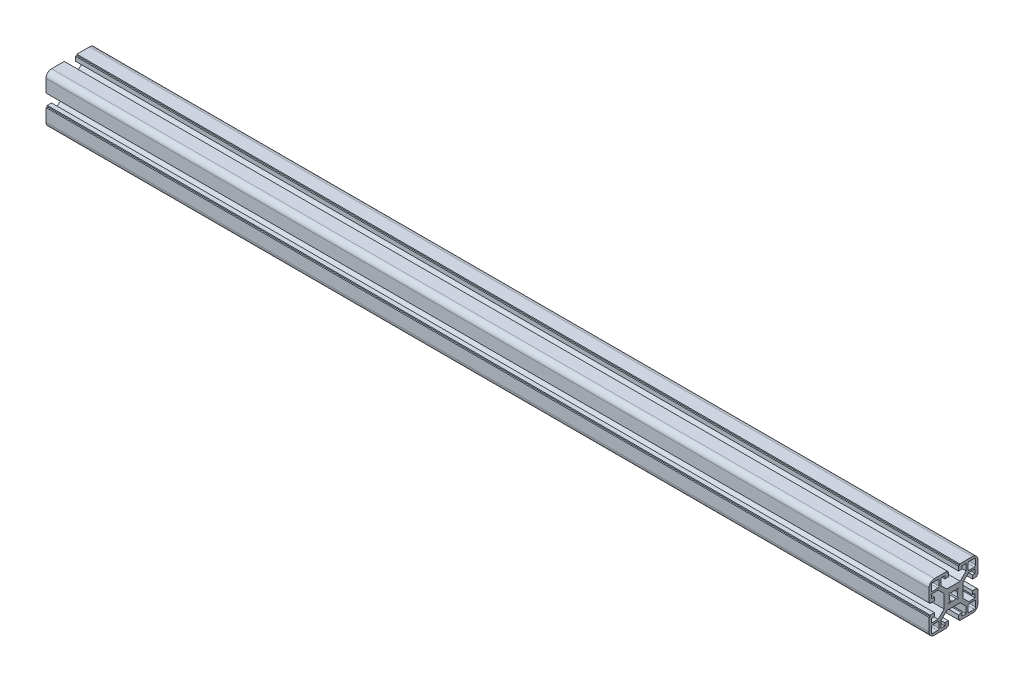
SolidWorks part; units mm, degrees
ref_plane "前视基准面" through (0, 0, 0) normal (0, 0, 1) x (1, 0, 0)
ref_plane "上视基准面" through (0, 0, 0) normal (0, 1, 0) x (1, 0, 0)
ref_plane "右视基准面" through (0, 0, 0) normal (1, 0, 0) x (0, 0, -1)
other "Configuration Table"
sketch "草图1" plane through (0, 0, 0) normal (1, 0, 0) x (0, 0, -1)
  line L0 (4.82, 19.28) -> (3.82, 19.28)
  line L1 (3.82, 19.28) -> (3.82, 15.78)
  line L2 (3.82, 15.78) -> (6.7364, 15.78)
  line L3 (6.7364, 15.78) -> (6.7364, 18.03)
  line L4 (6.7364, 18.03) -> (10.02, 18.03)
  line L5 (10.02, 18.03) -> (10.02, 12.7013)
  line L6 (10.02, 12.7013) -> (5.1987, 7.88)
  line L7 (5.1987, 7.88) -> (-5.7586, 7.88)
  line L8 (-5.7586, 7.88) -> (-10.58, 12.7013)
  line L9 (-10.58, 12.7013) -> (-10.58, 18.03)
  line L10 (-10.58, 18.03) -> (-7.2963, 18.03)
  line L11 (-7.2963, 18.03) -> (-7.2963, 15.78)
  line L12 (-7.2963, 15.78) -> (-4.38, 15.78)
  line L13 (-4.38, 15.78) -> (-4.38, 19.28)
  line L14 (-4.38, 19.28) -> (-5.38, 19.28)
  line L15 (-5.38, 19.28) -> (-5.38, 20.28)
  line L16 (-5.38, 20.28) -> (-15.78, 20.28)
  line L17 (-20.28, 15.78) -> (-20.28, 5.38)
  line L18 (-20.28, 5.38) -> (-19.28, 5.38)
  line L19 (-19.28, 5.38) -> (-19.28, 4.38)
  line L20 (-19.28, 4.38) -> (-15.78, 4.38)
  line L21 (-15.78, 4.38) -> (-15.78, 7.2963)
  line L22 (-15.78, 7.2963) -> (-18.03, 7.2963)
  line L23 (-18.03, 7.2963) -> (-18.03, 10.58)
  line L24 (-18.03, 10.58) -> (-12.7013, 10.58)
  line L25 (-12.7013, 10.58) -> (-7.88, 5.7586)
  line L26 (-7.88, 5.7586) -> (-7.88, -5.1987)
  line L27 (-7.88, -5.1987) -> (-12.7013, -10.02)
  line L28 (-12.7013, -10.02) -> (-18.03, -10.02)
  line L29 (-18.03, -10.02) -> (-18.03, -6.7364)
  line L30 (-18.03, -6.7364) -> (-15.78, -6.7364)
  line L31 (-15.78, -6.7364) -> (-15.78, -3.82)
  line L32 (-15.78, -3.82) -> (-19.28, -3.82)
  line L33 (-19.28, -3.82) -> (-19.28, -4.82)
  line L34 (-19.28, -4.82) -> (-20.28, -4.82)
  line L35 (-20.28, -4.82) -> (-20.28, -15.22)
  line L36 (-15.78, -19.72) -> (-5.38, -19.72)
  line L37 (-5.38, -19.72) -> (-5.38, -18.72)
  line L38 (-5.38, -18.72) -> (-4.38, -18.72)
  line L39 (-4.38, -18.72) -> (-4.38, -15.22)
  line L40 (-4.38, -15.22) -> (-7.2963, -15.22)
  line L41 (-7.2963, -15.22) -> (-7.2963, -17.47)
  line L42 (-7.2963, -17.47) -> (-10.58, -17.47)
  line L43 (-10.58, -17.47) -> (-10.58, -12.1414)
  line L44 (-10.58, -12.1414) -> (-5.7586, -7.32)
  line L45 (-5.7586, -7.32) -> (5.1987, -7.32)
  line L46 (5.1987, -7.32) -> (10.02, -12.1414)
  line L47 (10.02, -12.1414) -> (10.02, -17.47)
  line L48 (10.02, -17.47) -> (6.7364, -17.47)
  line L49 (6.7364, -17.47) -> (6.7364, -15.22)
  line L50 (6.7364, -15.22) -> (3.82, -15.22)
  line L51 (3.82, -15.22) -> (3.82, -18.72)
  line L52 (3.82, -18.72) -> (4.82, -18.72)
  line L53 (4.82, -18.72) -> (4.82, -19.72)
  line L54 (4.82, -19.72) -> (15.22, -19.72)
  line L55 (19.72, -15.22) -> (19.72, -4.82)
  line L56 (19.72, -4.82) -> (18.72, -4.82)
  line L57 (18.72, -4.82) -> (18.72, -3.82)
  line L58 (18.72, -3.82) -> (15.22, -3.82)
  line L59 (15.22, -3.82) -> (15.22, -6.7364)
  line L60 (15.22, -6.7364) -> (17.47, -6.7364)
  line L61 (17.47, -6.7364) -> (17.47, -10.02)
  line L62 (17.47, -10.02) -> (12.1414, -10.02)
  line L63 (12.1414, -10.02) -> (7.32, -5.1987)
  line L64 (7.32, -5.1987) -> (7.32, 5.7586)
  line L65 (7.32, 5.7586) -> (12.1414, 10.58)
  line L66 (12.1414, 10.58) -> (17.47, 10.58)
  line L67 (17.47, 10.58) -> (17.47, 7.2963)
  line L68 (17.47, 7.2963) -> (15.22, 7.2963)
  line L69 (15.22, 7.2963) -> (15.22, 4.38)
  line L70 (15.22, 4.38) -> (18.72, 4.38)
  line L71 (18.72, 4.38) -> (18.72, 5.38)
  line L72 (18.72, 5.38) -> (19.72, 5.38)
  line L73 (19.72, 5.38) -> (19.72, 15.78)
  line L74 (15.22, 20.28) -> (4.82, 20.28)
  line L75 (4.82, 20.28) -> (4.82, 19.28)
  line L76 (-13.08, -17.72) -> (-17.28, -17.72)
  line L77 (-18.28, -16.72) -> (-18.28, -12.52)
  line L78 (-17.28, -11.52) -> (-13.08, -11.52)
  line L79 (-12.08, -12.52) -> (-12.08, -16.72)
  line L80 (-17.28, 18.28) -> (-13.08, 18.28)
  line L81 (-12.08, 17.28) -> (-12.08, 13.08)
  line L82 (-13.08, 12.08) -> (-17.28, 12.08)
  line L83 (-18.28, 13.08) -> (-18.28, 17.28)
  line L84 (16.72, 12.08) -> (12.52, 12.08)
  line L85 (11.52, 13.08) -> (11.52, 17.28)
  line L86 (12.52, 18.28) -> (16.72, 18.28)
  line L87 (17.72, 17.28) -> (17.72, 13.08)
  line L88 (3.7505, -3.0434) -> (3.0434, -3.7505)
  line L89 (3.0434, -3.7505) -> (1.7445, -2.4516)
  line L90 (-2.3044, -2.4516) -> (-3.6033, -3.7505)
  line L91 (-3.6033, -3.7505) -> (-4.3104, -3.0434)
  line L92 (-4.3104, -3.0434) -> (-3.0115, -1.7445)
  line L93 (-3.0115, 2.3044) -> (-4.3104, 3.6033)
  line L94 (-4.3104, 3.6033) -> (-3.6033, 4.3104)
  line L95 (-3.6033, 4.3104) -> (-2.3044, 3.0115)
  line L96 (1.7445, 3.0115) -> (3.0434, 4.3104)
  line L97 (3.0434, 4.3104) -> (3.7505, 3.6033)
  line L98 (3.7505, 3.6033) -> (2.4516, 2.3044)
  line L99 (2.4516, -1.7445) -> (3.7505, -3.0434)
  line L100 (17.72, -12.52) -> (17.72, -16.72)
  line L101 (16.72, -17.72) -> (12.52, -17.72)
  line L102 (11.52, -16.72) -> (11.52, -12.52)
  line L103 (12.52, -11.52) -> (16.72, -11.52)
  arc A0 (-15.78, 20.28) -> (-20.28, 15.78) centre (-15.78, 15.78) ccw
  arc A1 (-20.28, -15.22) -> (-15.78, -19.72) centre (-15.78, -15.22) ccw
  arc A2 (15.22, -19.72) -> (19.72, -15.22) centre (15.22, -15.22) ccw
  arc A3 (19.72, 15.78) -> (15.22, 20.28) centre (15.22, 15.78) ccw
  arc A4 (-12.08, -16.72) -> (-13.08, -17.72) centre (-13.08, -16.72) cw
  arc A5 (-17.28, -17.72) -> (-18.28, -16.72) centre (-17.28, -16.72) cw
  arc A6 (-18.28, -12.52) -> (-17.28, -11.52) centre (-17.28, -12.52) cw
  arc A7 (-13.08, -11.52) -> (-12.08, -12.52) centre (-13.08, -12.52) cw
  arc A8 (-18.28, 17.28) -> (-17.28, 18.28) centre (-17.28, 17.28) cw
  arc A9 (-13.08, 18.28) -> (-12.08, 17.28) centre (-13.08, 17.28) cw
  arc A10 (-12.08, 13.08) -> (-13.08, 12.08) centre (-13.08, 13.08) cw
  arc A11 (-17.28, 12.08) -> (-18.28, 13.08) centre (-17.28, 13.08) cw
  arc A12 (17.72, 13.08) -> (16.72, 12.08) centre (16.72, 13.08) cw
  arc A13 (12.52, 12.08) -> (11.52, 13.08) centre (12.52, 13.08) cw
  arc A14 (11.52, 17.28) -> (12.52, 18.28) centre (12.52, 17.28) cw
  arc A15 (16.72, 18.28) -> (17.72, 17.28) centre (16.72, 17.28) cw
  arc A16 (1.7445, -2.4516) -> (-2.3044, -2.4516) centre (-0.28, 0.28) cw
  arc A17 (-3.0115, -1.7445) -> (-3.0115, 2.3044) centre (-0.28, 0.28) cw
  arc A18 (-2.3044, 3.0115) -> (1.7445, 3.0115) centre (-0.28, 0.28) cw
  arc A19 (2.4516, 2.3044) -> (2.4516, -1.7445) centre (-0.28, 0.28) cw
  arc A20 (16.72, -11.52) -> (17.72, -12.52) centre (16.72, -12.52) cw
  arc A21 (17.72, -16.72) -> (16.72, -17.72) centre (16.72, -16.72) cw
  arc A22 (12.52, -17.72) -> (11.52, -16.72) centre (12.52, -16.72) cw
  arc A23 (11.52, -12.52) -> (12.52, -11.52) centre (12.52, -12.52) cw
extrude "凸台-拉伸1" add sketch "草图1" against normal blind 50
sketch "草图2" plane through (0, 0, 0) normal (1, 0, 0) x (0, 0, -1)
  line L4 (-17.28, -17.72) -> (-13.08, -17.72)
  line L5 (-18.28, -12.52) -> (-18.28, -16.72)
  line L6 (-13.08, -11.52) -> (-17.28, -11.52)
  line L7 (-12.08, -16.72) -> (-12.08, -12.52)
  line L8 (-17.28, -17.72) -> (-13.08, -17.72)
  line L9 (-18.28, -12.52) -> (-18.28, -16.72)
  line L10 (-13.08, -11.52) -> (-17.28, -11.52)
  line L11 (-12.08, -16.72) -> (-12.08, -12.52)
  line L12 (-13.08, 18.28) -> (-17.28, 18.28)
  line L13 (-12.08, 13.08) -> (-12.08, 17.28)
  line L14 (-17.28, 12.08) -> (-13.08, 12.08)
  line L15 (-18.28, 17.28) -> (-18.28, 13.08)
  line L16 (-13.08, 18.28) -> (-17.28, 18.28)
  line L17 (-12.08, 13.08) -> (-12.08, 17.28)
  line L18 (-17.28, 12.08) -> (-13.08, 12.08)
  line L19 (-18.28, 17.28) -> (-18.28, 13.08)
  line L20 (11.52, 17.28) -> (11.52, 13.08)
  line L21 (16.72, 18.28) -> (12.52, 18.28)
  line L22 (17.72, 13.08) -> (17.72, 17.28)
  line L23 (12.52, 12.08) -> (16.72, 12.08)
  line L24 (11.52, 17.28) -> (11.52, 13.08)
  line L25 (16.72, 18.28) -> (12.52, 18.28)
  line L26 (17.72, 13.08) -> (17.72, 17.28)
  line L27 (12.52, 12.08) -> (16.72, 12.08)
  line L28 (11.52, -12.52) -> (11.52, -16.72)
  line L29 (16.72, -11.52) -> (12.52, -11.52)
  line L30 (17.72, -16.72) -> (17.72, -12.52)
  line L31 (12.52, -17.72) -> (16.72, -17.72)
  line L32 (11.52, -12.52) -> (11.52, -16.72)
  line L33 (16.72, -11.52) -> (12.52, -11.52)
  line L34 (17.72, -16.72) -> (17.72, -12.52)
  line L35 (12.52, -17.72) -> (16.72, -17.72)
  line L36 (-4.3104, 3.6033) -> (-3.0115, 2.3044)
  line L37 (-3.6033, 4.3104) -> (-4.3104, 3.6033)
  line L38 (-2.3044, 3.0115) -> (-3.6033, 4.3104)
  line L39 (3.0434, 4.3104) -> (1.7445, 3.0115)
  line L40 (3.7505, 3.6033) -> (3.0434, 4.3104)
  line L41 (2.4516, 2.3044) -> (3.7505, 3.6033)
  line L42 (3.7505, -3.0434) -> (2.4516, -1.7445)
  line L43 (3.0434, -3.7505) -> (3.7505, -3.0434)
  line L44 (1.7445, -2.4516) -> (3.0434, -3.7505)
  line L45 (-3.6033, -3.7505) -> (-2.3044, -2.4516)
  line L46 (-4.3104, -3.0434) -> (-3.6033, -3.7505)
  line L47 (-3.0115, -1.7445) -> (-4.3104, -3.0434)
  line L48 (-4.3104, 3.6033) -> (-3.0115, 2.3044)
  line L49 (-3.6033, 4.3104) -> (-4.3104, 3.6033)
  line L50 (-2.3044, 3.0115) -> (-3.6033, 4.3104)
  line L51 (3.0434, 4.3104) -> (1.7445, 3.0115)
  line L52 (3.7505, 3.6033) -> (3.0434, 4.3104)
  line L53 (2.4516, 2.3044) -> (3.7505, 3.6033)
  line L54 (3.7505, -3.0434) -> (2.4516, -1.7445)
  line L55 (3.0434, -3.7505) -> (3.7505, -3.0434)
  line L56 (1.7445, -2.4516) -> (3.0434, -3.7505)
  line L57 (-3.6033, -3.7505) -> (-2.3044, -2.4516)
  line L58 (-4.3104, -3.0434) -> (-3.6033, -3.7505)
  line L59 (-3.0115, -1.7445) -> (-4.3104, -3.0434)
  line L84 (19.72, 5.38) -> (19.72, 15.78)
  line L85 (18.72, 5.38) -> (19.72, 5.38)
  line L86 (18.72, 4.38) -> (18.72, 5.38)
  line L87 (15.22, 4.38) -> (18.72, 4.38)
  line L88 (15.22, 7.2963) -> (15.22, 4.38)
  line L89 (17.47, 7.2963) -> (15.22, 7.2963)
  line L90 (17.47, 10.58) -> (17.47, 7.2963)
  line L91 (12.1414, 10.58) -> (17.47, 10.58)
  line L92 (7.32, 5.7586) -> (12.1414, 10.58)
  line L93 (7.32, -5.1987) -> (7.32, 5.7586)
  line L94 (12.1414, -10.02) -> (7.32, -5.1987)
  line L95 (17.47, -10.02) -> (12.1414, -10.02)
  line L96 (17.47, -6.7364) -> (17.47, -10.02)
  line L97 (15.22, -6.7364) -> (17.47, -6.7364)
  line L98 (15.22, -3.82) -> (15.22, -6.7364)
  line L99 (18.72, -3.82) -> (15.22, -3.82)
  line L100 (18.72, -4.82) -> (18.72, -3.82)
  line L101 (19.72, -4.82) -> (18.72, -4.82)
  line L102 (19.72, -15.22) -> (19.72, -4.82)
  line L103 (4.82, -19.72) -> (15.22, -19.72)
  line L104 (4.82, -18.72) -> (4.82, -19.72)
  line L105 (3.82, -18.72) -> (4.82, -18.72)
  line L106 (3.82, -15.22) -> (3.82, -18.72)
  line L107 (6.7364, -15.22) -> (3.82, -15.22)
  line L108 (6.7364, -17.47) -> (6.7364, -15.22)
  line L109 (10.02, -17.47) -> (6.7364, -17.47)
  line L110 (10.02, -12.1414) -> (10.02, -17.47)
  line L111 (5.1987, -7.32) -> (10.02, -12.1414)
  line L112 (-5.7586, -7.32) -> (5.1987, -7.32)
  line L113 (-10.58, -12.1414) -> (-5.7586, -7.32)
  line L114 (-10.58, -17.47) -> (-10.58, -12.1414)
  line L115 (-7.2963, -17.47) -> (-10.58, -17.47)
  line L116 (-7.2963, -15.22) -> (-7.2963, -17.47)
  line L117 (-4.38, -15.22) -> (-7.2963, -15.22)
  line L118 (-4.38, -18.72) -> (-4.38, -15.22)
  line L119 (-5.38, -18.72) -> (-4.38, -18.72)
  line L120 (-5.38, -19.72) -> (-5.38, -18.72)
  line L121 (-15.78, -19.72) -> (-5.38, -19.72)
  line L122 (-20.28, -4.82) -> (-20.28, -15.22)
  line L123 (-19.28, -4.82) -> (-20.28, -4.82)
  line L124 (-19.28, -3.82) -> (-19.28, -4.82)
  line L125 (-15.78, -3.82) -> (-19.28, -3.82)
  line L126 (-15.78, -6.7364) -> (-15.78, -3.82)
  line L127 (-18.03, -6.7364) -> (-15.78, -6.7364)
  line L128 (-18.03, -10.02) -> (-18.03, -6.7364)
  line L129 (-12.7013, -10.02) -> (-18.03, -10.02)
  line L130 (-7.88, -5.1987) -> (-12.7013, -10.02)
  line L131 (-7.88, 5.7586) -> (-7.88, -5.1987)
  line L132 (-12.7013, 10.58) -> (-7.88, 5.7586)
  line L133 (-18.03, 10.58) -> (-12.7013, 10.58)
  line L134 (-18.03, 7.2963) -> (-18.03, 10.58)
  line L135 (-15.78, 7.2963) -> (-18.03, 7.2963)
  line L136 (-15.78, 4.38) -> (-15.78, 7.2963)
  line L137 (-19.28, 4.38) -> (-15.78, 4.38)
  line L138 (-19.28, 5.38) -> (-19.28, 4.38)
  line L139 (-20.28, 5.38) -> (-19.28, 5.38)
  line L140 (-20.28, 15.78) -> (-20.28, 5.38)
  line L141 (-5.38, 20.28) -> (-15.78, 20.28)
  line L142 (-5.38, 19.28) -> (-5.38, 20.28)
  line L143 (-4.38, 19.28) -> (-5.38, 19.28)
  line L144 (-4.38, 15.78) -> (-4.38, 19.28)
  line L145 (-7.2963, 15.78) -> (-4.38, 15.78)
  line L146 (-7.2963, 18.03) -> (-7.2963, 15.78)
  line L147 (-10.58, 18.03) -> (-7.2963, 18.03)
  line L148 (-10.58, 12.7013) -> (-10.58, 18.03)
  line L149 (-5.7586, 7.88) -> (-10.58, 12.7013)
  line L150 (5.1987, 7.88) -> (-5.7586, 7.88)
  line L151 (10.02, 12.7013) -> (5.1987, 7.88)
  line L152 (10.02, 18.03) -> (10.02, 12.7013)
  line L153 (6.7364, 18.03) -> (10.02, 18.03)
  line L154 (6.7364, 15.78) -> (6.7364, 18.03)
  line L155 (3.82, 15.78) -> (6.7364, 15.78)
  line L156 (3.82, 19.28) -> (3.82, 15.78)
  line L157 (4.82, 19.28) -> (3.82, 19.28)
  line L158 (4.82, 20.28) -> (4.82, 19.28)
  line L159 (15.22, 20.28) -> (4.82, 20.28)
  line L160 (19.72, 5.38) -> (19.72, 15.78)
  line L161 (18.72, 5.38) -> (19.72, 5.38)
  line L162 (18.72, 4.38) -> (18.72, 5.38)
  line L163 (15.22, 4.38) -> (18.72, 4.38)
  line L164 (15.22, 7.2963) -> (15.22, 4.38)
  line L165 (17.47, 7.2963) -> (15.22, 7.2963)
  line L166 (17.47, 10.58) -> (17.47, 7.2963)
  line L167 (12.1414, 10.58) -> (17.47, 10.58)
  line L168 (7.32, 5.7586) -> (12.1414, 10.58)
  line L169 (7.32, -5.1987) -> (7.32, 5.7586)
  line L170 (12.1414, -10.02) -> (7.32, -5.1987)
  line L171 (17.47, -10.02) -> (12.1414, -10.02)
  line L172 (17.47, -6.7364) -> (17.47, -10.02)
  line L173 (15.22, -6.7364) -> (17.47, -6.7364)
  line L174 (15.22, -3.82) -> (15.22, -6.7364)
  line L175 (18.72, -3.82) -> (15.22, -3.82)
  line L176 (18.72, -4.82) -> (18.72, -3.82)
  line L177 (19.72, -4.82) -> (18.72, -4.82)
  line L178 (19.72, -15.22) -> (19.72, -4.82)
  line L179 (4.82, -19.72) -> (15.22, -19.72)
  line L180 (4.82, -18.72) -> (4.82, -19.72)
  line L181 (3.82, -18.72) -> (4.82, -18.72)
  line L182 (3.82, -15.22) -> (3.82, -18.72)
  line L183 (6.7364, -15.22) -> (3.82, -15.22)
  line L184 (6.7364, -17.47) -> (6.7364, -15.22)
  line L185 (10.02, -17.47) -> (6.7364, -17.47)
  line L186 (10.02, -12.1414) -> (10.02, -17.47)
  line L187 (5.1987, -7.32) -> (10.02, -12.1414)
  line L188 (-5.7586, -7.32) -> (5.1987, -7.32)
  line L189 (-10.58, -12.1414) -> (-5.7586, -7.32)
  line L190 (-10.58, -17.47) -> (-10.58, -12.1414)
  line L191 (-7.2963, -17.47) -> (-10.58, -17.47)
  line L192 (-7.2963, -15.22) -> (-7.2963, -17.47)
  line L193 (-4.38, -15.22) -> (-7.2963, -15.22)
  line L194 (-4.38, -18.72) -> (-4.38, -15.22)
  line L195 (-5.38, -18.72) -> (-4.38, -18.72)
  line L196 (-5.38, -19.72) -> (-5.38, -18.72)
  line L197 (-15.78, -19.72) -> (-5.38, -19.72)
  line L198 (-20.28, -4.82) -> (-20.28, -15.22)
  line L199 (-19.28, -4.82) -> (-20.28, -4.82)
  line L200 (-19.28, -3.82) -> (-19.28, -4.82)
  line L201 (-15.78, -3.82) -> (-19.28, -3.82)
  line L202 (-15.78, -6.7364) -> (-15.78, -3.82)
  line L203 (-18.03, -6.7364) -> (-15.78, -6.7364)
  line L204 (-18.03, -10.02) -> (-18.03, -6.7364)
  line L205 (-12.7013, -10.02) -> (-18.03, -10.02)
  line L206 (-7.88, -5.1987) -> (-12.7013, -10.02)
  line L207 (-7.88, 5.7586) -> (-7.88, -5.1987)
  line L208 (-12.7013, 10.58) -> (-7.88, 5.7586)
  line L209 (-18.03, 10.58) -> (-12.7013, 10.58)
  line L210 (-18.03, 7.2963) -> (-18.03, 10.58)
  line L211 (-15.78, 7.2963) -> (-18.03, 7.2963)
  line L212 (-15.78, 4.38) -> (-15.78, 7.2963)
  line L213 (-19.28, 4.38) -> (-15.78, 4.38)
  line L214 (-19.28, 5.38) -> (-19.28, 4.38)
  line L215 (-20.28, 5.38) -> (-19.28, 5.38)
  line L216 (-20.28, 15.78) -> (-20.28, 5.38)
  line L217 (-5.38, 20.28) -> (-15.78, 20.28)
  line L218 (-5.38, 19.28) -> (-5.38, 20.28)
  line L219 (-4.38, 19.28) -> (-5.38, 19.28)
  line L220 (-4.38, 15.78) -> (-4.38, 19.28)
  line L221 (-7.2963, 15.78) -> (-4.38, 15.78)
  line L222 (-7.2963, 18.03) -> (-7.2963, 15.78)
  line L223 (-10.58, 18.03) -> (-7.2963, 18.03)
  line L224 (-10.58, 12.7013) -> (-10.58, 18.03)
  line L225 (-5.7586, 7.88) -> (-10.58, 12.7013)
  line L226 (5.1987, 7.88) -> (-5.7586, 7.88)
  line L227 (10.02, 12.7013) -> (5.1987, 7.88)
  line L228 (10.02, 18.03) -> (10.02, 12.7013)
  line L229 (6.7364, 18.03) -> (10.02, 18.03)
  line L230 (6.7364, 15.78) -> (6.7364, 18.03)
  line L231 (3.82, 15.78) -> (6.7364, 15.78)
  line L232 (3.82, 19.28) -> (3.82, 15.78)
  line L233 (4.82, 19.28) -> (3.82, 19.28)
  line L234 (4.82, 20.28) -> (4.82, 19.28)
  line L235 (15.22, 20.28) -> (4.82, 20.28)
  arc A4 (-18.28, -16.72) -> (-17.28, -17.72) centre (-17.28, -16.72) ccw
  arc A5 (-17.28, -11.52) -> (-18.28, -12.52) centre (-17.28, -12.52) ccw
  arc A6 (-12.08, -12.52) -> (-13.08, -11.52) centre (-13.08, -12.52) ccw
  arc A7 (-13.08, -17.72) -> (-12.08, -16.72) centre (-13.08, -16.72) ccw
  arc A8 (-18.28, -16.72) -> (-17.28, -17.72) centre (-17.28, -16.72) ccw
  arc A9 (-17.28, -11.52) -> (-18.28, -12.52) centre (-17.28, -12.52) ccw
  arc A10 (-12.08, -12.52) -> (-13.08, -11.52) centre (-13.08, -12.52) ccw
  arc A11 (-13.08, -17.72) -> (-12.08, -16.72) centre (-13.08, -16.72) ccw
  arc A12 (15.22, -19.72) -> (19.72, -15.22) centre (15.22, -15.22) ccw
  arc A13 (-20.28, -15.22) -> (-15.78, -19.72) centre (-15.78, -15.22) ccw
  arc A14 (-15.78, 20.28) -> (-20.28, 15.78) centre (-15.78, 15.78) ccw
  arc A15 (19.72, 15.78) -> (15.22, 20.28) centre (15.22, 15.78) ccw
  arc A16 (15.22, -19.72) -> (19.72, -15.22) centre (15.22, -15.22) ccw
  arc A17 (-20.28, -15.22) -> (-15.78, -19.72) centre (-15.78, -15.22) ccw
  arc A18 (-15.78, 20.28) -> (-20.28, 15.78) centre (-15.78, 15.78) ccw
  arc A19 (19.72, 15.78) -> (15.22, 20.28) centre (15.22, 15.78) ccw
  arc A20 (-12.08, 17.28) -> (-13.08, 18.28) centre (-13.08, 17.28) ccw
  arc A21 (-13.08, 12.08) -> (-12.08, 13.08) centre (-13.08, 13.08) ccw
  arc A22 (-18.28, 13.08) -> (-17.28, 12.08) centre (-17.28, 13.08) ccw
  arc A23 (-17.28, 18.28) -> (-18.28, 17.28) centre (-17.28, 17.28) ccw
  arc A24 (-12.08, 17.28) -> (-13.08, 18.28) centre (-13.08, 17.28) ccw
  arc A25 (-13.08, 12.08) -> (-12.08, 13.08) centre (-13.08, 13.08) ccw
  arc A26 (-18.28, 13.08) -> (-17.28, 12.08) centre (-17.28, 13.08) ccw
  arc A27 (-17.28, 18.28) -> (-18.28, 17.28) centre (-17.28, 17.28) ccw
  arc A28 (12.52, 18.28) -> (11.52, 17.28) centre (12.52, 17.28) ccw
  arc A29 (17.72, 17.28) -> (16.72, 18.28) centre (16.72, 17.28) ccw
  arc A30 (16.72, 12.08) -> (17.72, 13.08) centre (16.72, 13.08) ccw
  arc A31 (11.52, 13.08) -> (12.52, 12.08) centre (12.52, 13.08) ccw
  arc A32 (12.52, 18.28) -> (11.52, 17.28) centre (12.52, 17.28) ccw
  arc A33 (17.72, 17.28) -> (16.72, 18.28) centre (16.72, 17.28) ccw
  arc A34 (16.72, 12.08) -> (17.72, 13.08) centre (16.72, 13.08) ccw
  arc A35 (11.52, 13.08) -> (12.52, 12.08) centre (12.52, 13.08) ccw
  arc A36 (1.7445, 3.0115) -> (-2.3044, 3.0115) centre (-0.28, 0.28) ccw
  arc A37 (2.4516, -1.7445) -> (2.4516, 2.3044) centre (-0.28, 0.28) ccw
  arc A38 (-2.3044, -2.4516) -> (1.7445, -2.4516) centre (-0.28, 0.28) ccw
  arc A39 (-3.0115, 2.3044) -> (-3.0115, -1.7445) centre (-0.28, 0.28) ccw
  arc A40 (1.7445, 3.0115) -> (-2.3044, 3.0115) centre (-0.28, 0.28) ccw
  arc A41 (2.4516, -1.7445) -> (2.4516, 2.3044) centre (-0.28, 0.28) ccw
  arc A42 (-2.3044, -2.4516) -> (1.7445, -2.4516) centre (-0.28, 0.28) ccw
  arc A43 (-3.0115, 2.3044) -> (-3.0115, -1.7445) centre (-0.28, 0.28) ccw
  arc A44 (12.52, -11.52) -> (11.52, -12.52) centre (12.52, -12.52) ccw
  arc A45 (17.72, -12.52) -> (16.72, -11.52) centre (16.72, -12.52) ccw
  arc A46 (16.72, -17.72) -> (17.72, -16.72) centre (16.72, -16.72) ccw
  arc A47 (11.52, -16.72) -> (12.52, -17.72) centre (12.52, -16.72) ccw
  arc A48 (12.52, -11.52) -> (11.52, -12.52) centre (12.52, -12.52) ccw
  arc A49 (17.72, -12.52) -> (16.72, -11.52) centre (16.72, -12.52) ccw
  arc A50 (16.72, -17.72) -> (17.72, -16.72) centre (16.72, -16.72) ccw
  arc A51 (11.52, -16.72) -> (12.52, -17.72) centre (12.52, -16.72) ccw
  dimension "D1" = 0
  dimension "D2" = 0
  dimension "D3" = 0
  dimension "D4" = 0
  dimension "D5" = 0
  dimension "D6" = 0
extrude "凸台-拉伸2" add sketch "草图2" against normal blind 720
